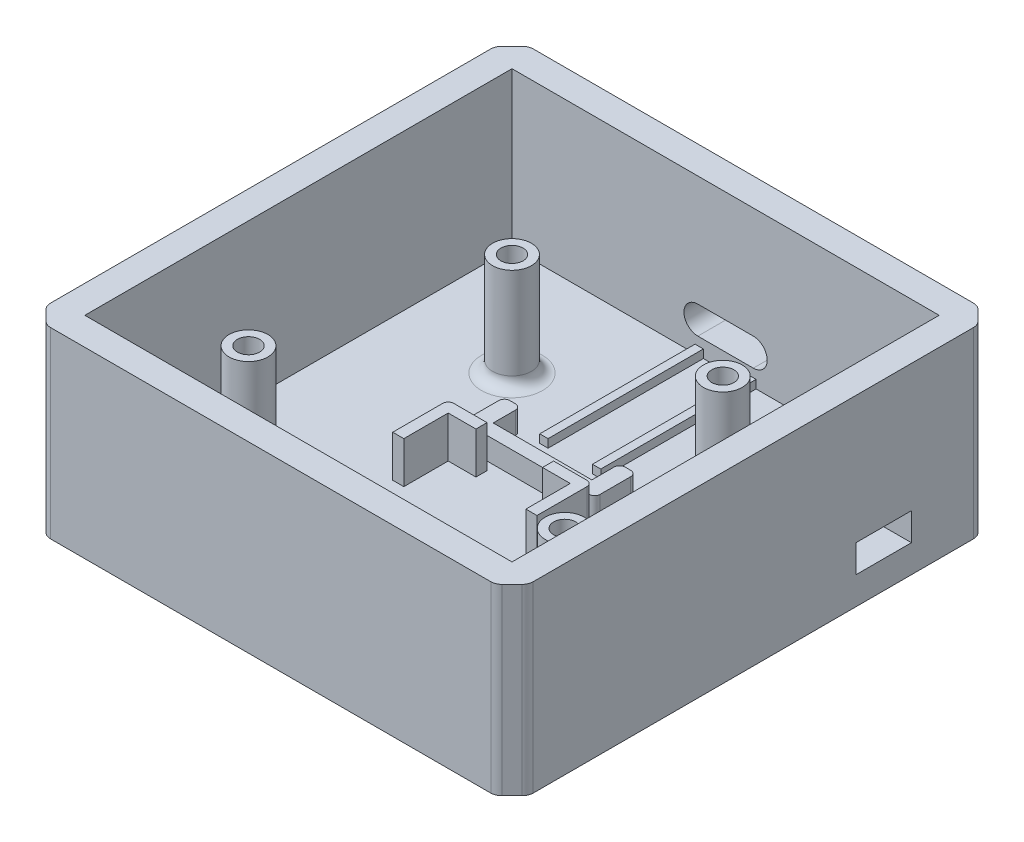
SolidWorks part; units mm, degrees
ref_plane "Front Plane" through (0, 0, 0) normal (0, 0, 1) x (1, 0, 0)
ref_plane "Top Plane" through (0, 0, 0) normal (0, 1, 0) x (1, 0, 0)
ref_plane "Right Plane" through (0, 0, 0) normal (1, 0, 0) x (0, 0, -1)
sketch "Sketch1" plane through (0, 0, 0) normal (0, 1, 0) x (1, 0, 0)
  line L1 (-38.5, -38.5) -> (38.5, -38.5)
  line L2 (-38.5, -38.5) -> (-38.5, 38.5)
  line L3 (-38.5, 38.5) -> (38.5, 38.5)
  line L4 (38.5, -38.5) -> (38.5, 38.5)
  line L5 (-38.5, -38.5) -> (38.5, 38.5) construction
  line L6 (-38.5, 38.5) -> (38.5, -38.5) construction
  point P0 (0, 0)
  dimension "D1" = 77
extrude "Boss-Extrude1" add sketch "Sketch1" along normal blind 5
sketch "Sketch2" plane through (0, 0, 0) normal (0, 1, 0) x (1, 0, 0)
  line L20 (38.5, -38.5) -> (38.5, 38.5) construction
  line L21 (38.5, 38.5) -> (-38.5, 38.5) construction
  line L22 (-38.5, 38.5) -> (-38.5, -38.5) construction
  line L23 (-38.5, -38.5) -> (38.5, -38.5) construction
  line L24 (43.5, -43.5) -> (43.5, 43.5)
  line L25 (43.5, 43.5) -> (-43.5, 43.5)
  line L26 (-43.5, 43.5) -> (-43.5, -43.5)
  line L27 (-43.5, -43.5) -> (43.5, -43.5)
  line L28 (43.5, -43.5) -> (43.5, 43.5)
  line L29 (43.5, 43.5) -> (-43.5, 43.5)
  line L30 (-43.5, 43.5) -> (-43.5, -43.5)
  line L31 (-43.5, -43.5) -> (43.5, -43.5)
  line L32 (38.5, -38.5) -> (38.5, 38.5)
  line L33 (38.5, 38.5) -> (-38.5, 38.5)
  line L34 (-38.5, 38.5) -> (-38.5, -38.5)
  line L35 (-38.5, -38.5) -> (38.5, -38.5)
  dimension "D1" = 5
extrude "Boss-Extrude2" add sketch "Sketch2" along normal blind 33
sketch "Sketch3" plane through (0, 5, 0) normal (0, 1, 0) x (1, 0, 0)
  line L0 (28.5, -19) -> (-28.5, -19) construction
  line L2 (19, 19) -> (-19, 19) construction
  circle A2 centre (-28.5, -19) radius 2
  circle A3 centre (28.5, -19) radius 2
  circle A4 centre (19, 19) radius 2
  circle A5 centre (-19, 19) radius 2
  circle A6 centre (-28.5, -19) radius 3.5
  circle A7 centre (-19, 19) radius 3.5
  circle A8 centre (28.5, -19) radius 3.5
  circle A9 centre (19, 19) radius 3.5
  point P0 (0, 0)
  point P2 (0, 19)
  point P17 (0, -19)
  dimension "D3" = 1.5
  dimension "D4" = 19
  dimension "D1" = 4
  dimension "D2" = 38
  dimension "D5" = 57
  dimension "D6" = 19
extrude "Boss-Extrude4" add sketch "Sketch3" along normal offset from surface (18.5 mm away) 9.5 up to face at (0, 33, 0)
sketch "Sketch11" plane through (0, 5, 0) normal (0, 1, 0) x (1, 0, 0)
  line L0 (-10, -31.5) -> (-10, -1.5)
  line L6 (-11, -32.5) -> (11, -32.5)
  line L7 (-11, -32.5) -> (-11, -0.5)
  line L8 (-11, -0.5) -> (11, -0.5)
  line L9 (11, -32.5) -> (11, -0.5)
  line L10 (-11, -32.5) -> (11, -0.5) construction
  line L11 (-11, -0.5) -> (11, -32.5) construction
  line L12 (38.5, 38.5) -> (-38.5, 38.5) construction
  line L13 (-8.89, 38.5) -> (8.89, 38.5) construction
  line L14 (-8.89, 38.5) -> (-8.89, 5.5) construction
  line L15 (-8.89, 5.5) -> (8.89, 5.5) construction
  line L16 (8.89, 38.5) -> (8.89, 5.5) construction
  line L17 (-8.89, 38.5) -> (8.89, 5.5) construction
  line L18 (-8.89, 5.5) -> (8.89, 38.5) construction
  line L27 (-10, -1.5) -> (10, -1.5)
  line L28 (10, -31.5) -> (10, -1.5)
  line L29 (-10, -31.5) -> (10, -31.5)
  line L30 (0, -18.15) -> (0, 18.15) construction
  line L31 (4, 38.5) -> (5.5, 38.5)
  line L32 (4, 38.5) -> (4, 10.5)
  line L33 (4, 10.5) -> (5.5, 10.5)
  line L34 (5.5, 38.5) -> (5.5, 10.5)
  line L35 (-4, 10.5) -> (-5.5, 10.5)
  line L36 (-5.5, 38.5) -> (-5.5, 10.5)
  line L37 (-4, 38.5) -> (-5.5, 38.5)
  line L38 (-4, 38.5) -> (-4, 10.5)
  line L39 (-38.5, -38.5) -> (38.5, -38.5) construction
  point P1 (0, 22)
  point P6 (0, -16.5)
  dimension "D1" = 33
  dimension "D2" = 17.78
  dimension "D3" = 1
  dimension "D4" = 20
  dimension "D5" = 6
  dimension "D6" = 30
  dimension "D7" = 4
  dimension "D8" = 1.5
  dimension "D9" = 5
extrude "Boss-Extrude7" add sketch "Sketch11" along normal blind 1.5 contours L35 L36 L37 L38 | L32 L31 L34 L33
sketch "Sketch17" plane through (0, 5, 0) normal (0, 1, 0) x (1, 0, 0)
  line L0 (-8.89, 10.5) -> (-8.89, 5.5)
  line L1 (-8.89, 38.5) -> (-8.89, 5.5) construction
  line L2 (-8.89, 5.5) -> (8.89, 5.5)
  line L3 (8.89, 5.5) -> (8.89, 10.5)
  line L4 (8.89, 38.5) -> (8.89, 5.5) construction
  line L5 (8.89, 10.5) -> (11.89, 10.5)
  line L6 (11.89, 10.5) -> (11.89, 3)
  line L7 (11.89, 3) -> (-11.89, 3)
  line L8 (-11.89, 3) -> (-11.89, 10.5)
  line L9 (-11.89, 10.5) -> (-8.89, 10.5)
  dimension "D1" = 3
  dimension "D2" = 2.5
  dimension "D3" = 5
extrude "Boss-Extrude8" add sketch "Sketch17" along normal blind 4
sketch "Sketch4" plane through (0, 0, 0) normal (1, 0, 0) x (0, 0, -1)
  line L0 (0, 0) -> (0, 33) construction
  line L1 (-43.5, 33) -> (43.5, 33) construction
sketch "Sketch7" plane through (0, 0, 0) normal (0, -1, 0) x (1, 0, 0)
  line L0 (43.5, -43.5) -> (-43.5, -43.5) construction
  line L1 (-43.5, -43.5) -> (-43.5, 43.5) construction
  line L2 (0, 0) -> (-27.5, -27.5) construction
  circle A0 centre (-27.5, -27.5) radius 4
  circle A1 centre (-27.5, 27.5) radius 4
  circle A2 centre (27.5, 27.5) radius 4
  circle A3 centre (27.5, -27.5) radius 4
  dimension "D1" = 8
  dimension "D4" = 4
extrude "Cut-Extrude1" cut sketch "Sketch7" against normal blind 2
sketch "Sketch10" plane through (0, 0, -38.5) normal (0, 0, -1) x (-1, 0, 0)
  line L0 (-5, 10.5) -> (5, 10.5) construction
  line L1 (-5, 13) -> (5, 13)
  line L2 (-5, 8) -> (5, 8)
  line L3 (-38.5, 5) -> (-5.5, 5) construction
  line L4 (-38.5, 5) -> (-5.5, 5) construction
  line L5 (4, 6.5) -> (5.5, 6.5) construction
  arc A1 (-5, 13) -> (-5, 8) centre (-5, 10.5) ccw
  arc A2 (5, 8) -> (5, 13) centre (5, 10.5) ccw
  point P2 (0, 10.5)
  dimension "D1" = 10
  dimension "D2" = 5
  dimension "D3" = 4
extrude "Cut-Extrude2" cut sketch "Sketch10" along normal up to surface (5 mm away) up to face at (0, 16.5, -43.5)
sketch "Sketch16" plane through (38.5, 0, 0) normal (-1, 0, 0) x (0, 0, 1)
  line L0 (38.5, 5) -> (-38.5, 5) construction
  line L1 (-28.5, 5) -> (-18.5, 5)
  line L2 (-28.5, 5) -> (-28.5, 10)
  line L3 (-28.5, 10) -> (-18.5, 10)
  line L4 (-18.5, 5) -> (-18.5, 10)
  dimension "D1" = 10
  dimension "D2" = 5
  dimension "D3" = 10
extrude "Cut-Extrude3" cut sketch "Sketch16" against normal up to surface (5 mm away) up to face at (43.5, 16.5, 0)
sketch "Sketch15" plane through (0, 5, 0) normal (0, 1, 0) x (1, 0, 0)
  line L0 (-11, -0.5) -> (-11, -8.5)
  line L1 (-11, -32.5) -> (-11, -0.5) construction
  line L2 (-11, -8.5) -> (-13, -8.5)
  line L3 (-13, -8.5) -> (-13, 1.5)
  line L4 (-13, 1.5) -> (-6, 1.5)
  line L5 (-6, 1.5) -> (-6, -0.5)
  line L6 (-11, -0.5) -> (11, -0.5) construction
  line L7 (-6, -0.5) -> (-11, -0.5)
  line L8 (-13, -24.5) -> (-11, -24.5)
  line L9 (-11, -24.5) -> (-11, -32.5)
  line L10 (-11, -32.5) -> (-6, -32.5)
  line L11 (-11, -32.5) -> (11, -32.5) construction
  line L12 (-6, -32.5) -> (-6, -34.5)
  line L13 (-6, -34.5) -> (-13, -34.5)
  line L14 (-13, -24.5) -> (-13, -34.5)
  line L15 (0, -18.15) -> (0, 18.15) construction
  line L16 (13, -24.5) -> (11, -24.5)
  line L17 (11, -24.5) -> (11, -32.5)
  line L18 (11, -32.5) -> (6, -32.5)
  line L19 (6, -32.5) -> (6, -34.5)
  line L20 (6, -34.5) -> (13, -34.5)
  line L21 (13, -24.5) -> (13, -34.5)
  line L22 (6, 1.5) -> (6, -0.5)
  line L23 (13, 1.5) -> (6, 1.5)
  line L24 (13, -8.5) -> (13, 1.5)
  line L25 (11, -8.5) -> (13, -8.5)
  line L26 (11, -0.5) -> (11, -8.5)
  line L27 (6, -0.5) -> (11, -0.5)
  dimension "D1" = 7
  dimension "D2" = 10
  dimension "D4" = 2
extrude "Boss-Extrude6" add sketch "Sketch15" along normal blind 7.5 contours L7 L0 L2 L3 L4 L5 | L22 L27 L26 L25 L24 L23 | L14 L13 L12 L10 L9 L8 | L16 L17 L18 L19 L20 L21
fillet "Fillet1" radius 2 4 edges at (28.5, 5, 15.5) (19, 5, -22.5) (-28.5, 5, 15.5) (-19, 5, -22.5)
fillet "Fillet2" radius 1 10 edges at (-13, 8.75, 34.5) (13, 8.75, 34.5) (13, 8.75, -1.5) (-13, 8.75, -1.5) (-11.89, 7, -10.5) (11.89, 7, -10.5) (11.89, 7, -3) (-11.89, 7, -3) (8.89, 7, -10.5) (-8.89, 7, -10.5)
chamfer "Chamfer1" distance 3 angle 45 4 edges at (43.5, 16.5, -43.5) (-43.5, 16.5, 43.5) (43.5, 16.5, 43.5) (-43.5, 16.5, -43.5)
fillet "Fillet3" radius 2 8 edges at (-43.5, 16.5, -40.5) (-40.5, 16.5, -43.5) (40.5, 16.5, -43.5) (43.5, 16.5, -40.5) (43.5, 16.5, 40.5) (40.5, 16.5, 43.5) (-40.5, 16.5, 43.5) (-43.5, 16.5, 40.5)
